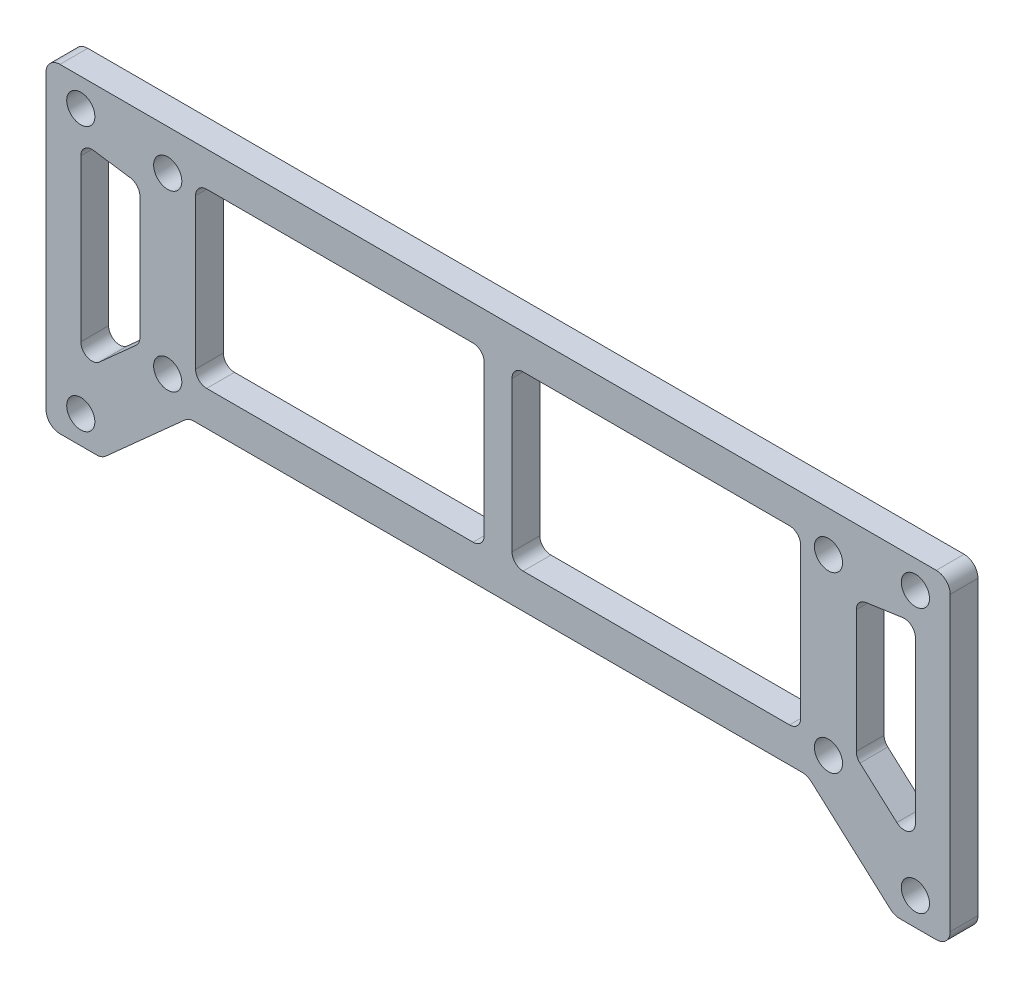
SolidWorks part; units mm, degrees
material "Thornel Mat VMA"
ref_plane "前视基准面" through (0, 0, 0) normal (0, 0, 1) x (1, 0, 0)
ref_plane "上视基准面" through (0, 0, 0) normal (0, 1, 0) x (1, 0, 0)
ref_plane "右视基准面" through (0, 0, 0) normal (1, 0, 0) x (0, 0, -1)
other "Configuration Table"
sketch "草图1" plane through (0, 0, 0) normal (0, 0, 1) x (1, 0, 0)
  line L1 (-65, -23) -> (65, -23)
  line L2 (-65, -23) -> (-65, 23)
  line L3 (-65, 23) -> (65, 23)
  line L4 (65, -23) -> (65, 23)
  line L5 (-65, -23) -> (65, 23) construction
  line L6 (-65, 23) -> (65, -23) construction
  point P0 (0, 0)
  dimension "D1" = 130
  dimension "D2" = 46
extrude "凸台-拉伸1" add sketch "草图1" along normal mid plane 4
sketch "草图3" plane through (0, 0, -2) normal (0, 0, -1) x (-1, 0, 0)
  circle A0 centre (-60, 19) radius 2.025 construction
  circle A1 centre (-60, -19) radius 2.025 construction
  circle A2 centre (60, 19) radius 2.025 construction
  circle A3 centre (60, -19) radius 2.025 construction
  circle A4 centre (-60, 19) radius 2.025
  circle A5 centre (-60, -19) radius 2.025
  circle A6 centre (60, 19) radius 2.025
  circle A7 centre (60, -19) radius 2.025
extrude "切除-拉伸1" cut sketch "草图3" against normal mid plane 160
sketch "草图4" plane through (0, 0, 2) normal (0, 0, 1) x (1, 0, 0)
  line L0 (0, 0) -> (0, 48.8174) construction
  circle A0 centre (47.5, 17.2) radius 1.65 construction
  circle A1 centre (47.5, -7.8) radius 1.65 construction
  circle A2 centre (47.5, 17.2) radius 1.65 construction
  circle A3 centre (47.5, -7.8) radius 1.65 construction
  circle A4 centre (47.5, 17.2) radius 2.025
  circle A5 centre (47.5, -7.8) radius 2.025
  circle A6 centre (-47.5, -7.8) radius 1.65 construction
  circle A7 centre (-47.5, 17.2) radius 1.65 construction
  circle A8 centre (-47.5, -7.8) radius 2.025
  circle A9 centre (-47.5, 17.2) radius 2.025
  dimension "D1" = 4.05
extrude "切除-拉伸2" cut sketch "草图4" against normal mid plane 160
sketch "草图5" plane through (0, 0, 2) normal (0, 0, 1) x (1, 0, 0)
  line L0 (-56.9716, -23) -> (-44.4716, -11.8)
  line L1 (-65, -23) -> (65, -23) construction
  line L2 (-44.4716, -11.8) -> (44.4716, -11.8)
  line L3 (44.4716, -11.8) -> (56.9716, -23)
  line L4 (56.9716, -23) -> (-56.9716, -23)
  line L5 (-60, -19) -> (-47.5, -7.8) construction
  line L6 (0, 0) -> (0, -11.8) construction
  line L7 (0, -11.8) -> (0, -23) construction
  circle A0 centre (47.5, -7.8) radius 2.025 construction
  dimension "D1" = 5
  dimension "D2" = 4
extrude "切除-拉伸3" cut sketch "草图5" against normal blind 10
sketch "草图6" plane through (0, 0, 2) normal (0, 0, 1) x (1, 0, 0)
  line L0 (0, 5.6) -> (0, 0) construction
  line L1 (-43.5, -6.8) -> (43.5, -6.8)
  line L2 (-43.5, -6.8) -> (-43.5, 18)
  line L3 (-43.5, 18) -> (43.5, 18)
  line L4 (43.5, -6.8) -> (43.5, 18)
  line L5 (-43.5, -6.8) -> (43.5, 18) construction
  line L6 (-43.5, 18) -> (43.5, -6.8) construction
  line L7 (65, 23) -> (-65, 23) construction
  line L8 (44.4716, -11.8) -> (-44.4716, -11.8) construction
  line L9 (0, 18) -> (0, -6.8) construction
  line L10 (-2, 18) -> (-2, -6.8)
  line L11 (2, 18) -> (2, -6.8)
  circle A0 centre (47.5, 17.2) radius 2.025 construction
  point P0 (0, 5.6)
  dimension "D1" = 5
  dimension "D2" = 5
  dimension "D3" = 4
  dimension "D4" = 2
  dimension "D5" = 2
extrude "切除-拉伸4" cut sketch "草图6" against normal blind 10 contours L10 L3 L2 L1 | L3 L11 L1 L4
sketch "草图7" plane through (0, 0, 2) normal (0, 0, 1) x (1, 0, 0)
  line L0 (-60, 14.9587) -> (-51.5, 13.7347)
  line L1 (-51.5, 13.7347) -> (-51.5, -6.0132)
  line L2 (-51.5, -6.0132) -> (-60, -13.6292)
  line L3 (-60, -13.6292) -> (-60, 14.9587)
  line L4 (-65, 23) -> (-65, -23) construction
  line L5 (-60, 19) -> (-47.5, 17.2) construction
  line L6 (-44.4716, -11.8) -> (-56.9716, -23) construction
  line L7 (0, 0) -> (0, 23) construction
  line L8 (65, 23) -> (-65, 23) construction
  line L9 (51.5, -6.0132) -> (60, -13.6292)
  line L10 (51.5, 13.7347) -> (51.5, -6.0132)
  line L11 (60, 14.9587) -> (51.5, 13.7347)
  line L12 (60, -13.6292) -> (60, 14.9587)
  circle A0 centre (-47.5, 17.2) radius 2.025 construction
  circle A1 centre (-47.5, -7.8) radius 2.025 construction
  point P16 (-53.75, 18.1)
  dimension "D1" = 5
  dimension "D2" = 4
  dimension "D3" = 4
  dimension "D4" = 4
extrude "切除-拉伸5" cut sketch "草图7" against normal blind 10
fillet "圆角1" radius 1.6 16 edges at (-2, 18, 0) (-2, -6.8, 0) (43.5, -6.8, 0) (2, -6.8, 0) (2, 18, 0) (43.5, 18, 0) (51.5, 13.7347, 0) (60, 14.9587, 0) (60, -13.6292, 0) (51.5, -6.0132, 0) (-60, 14.9587, 0) (-51.5, 13.7347, 0) (-51.5, -6.0132, 0) (-60, -13.6292, 0) (-43.5, -6.8, 0) (-43.5, 18, 0)
fillet "圆角2" radius 2 8 edges at (65, 23, 0) (65, -23, 0) (56.9716, -23, 0) (44.4716, -11.8, 0) (-44.4716, -11.8, 0) (-56.9716, -23, 0) (-65, -23, 0) (-65, 23, 0)
